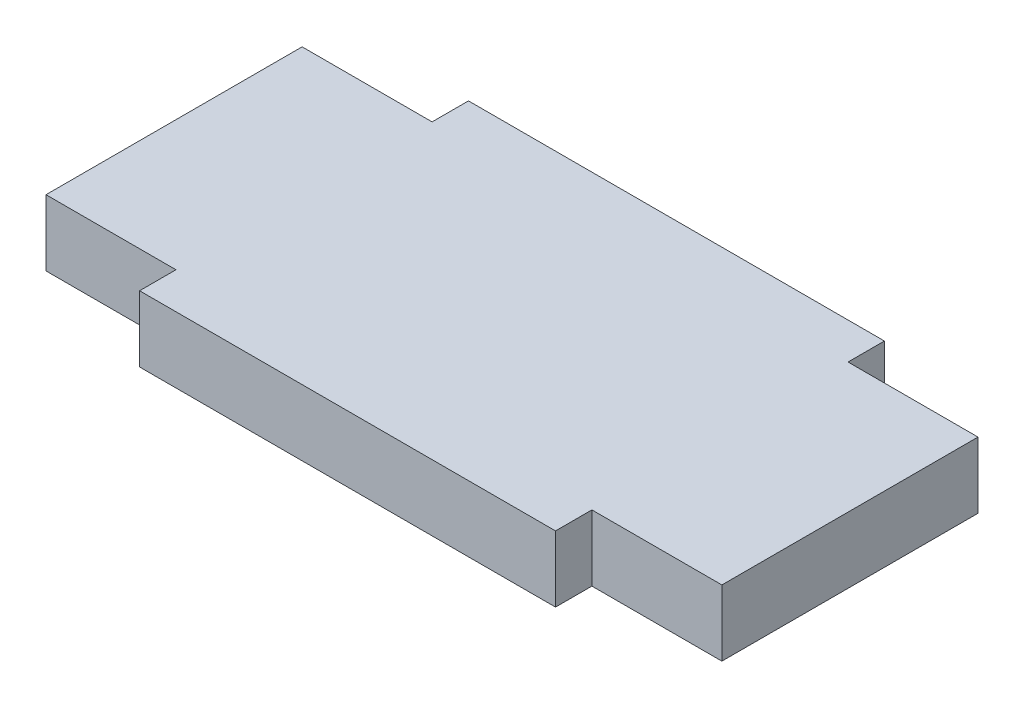
SolidWorks part; units mm, degrees
material "Acrylic (Medium-high impact)"
ref_plane "Front Plane" through (0, 0, 0) normal (0, 0, 1) x (1, 0, 0)
ref_plane "Top Plane" through (0, 0, 0) normal (0, 1, 0) x (1, 0, 0)
ref_plane "Right Plane" through (0, 0, 0) normal (1, 0, 0) x (0, 0, -1)
sketch "Sketch1" plane through (0, 0, 0) normal (0, 1, 0) x (1, 0, 0)
  line L0 (0, -55) -> (0, 55) construction
  line L1 (-32, 20.645) -> (33, 20.645)
  line L2 (-32, 20.645) -> (-32, -10.985)
  line L3 (-32, -10.985) -> (33, -10.985)
  line L4 (33, 20.645) -> (33, -10.985)
  line L7 (33, 20.645) -> (20.5, 20.645)
  line L8 (33, 20.645) -> (33, 17.145)
  line L9 (33, 17.145) -> (20.5, 17.145)
  line L10 (20.5, 20.645) -> (20.5, 17.145)
  line L11 (-32, 20.645) -> (-19.5, 20.645)
  line L12 (-32, 20.645) -> (-32, 17.145)
  line L13 (-32, 17.145) -> (-19.5, 17.145)
  line L14 (-19.5, 20.645) -> (-19.5, 17.145)
  line L15 (-32, -10.985) -> (-19.5, -10.985)
  line L16 (-32, -10.985) -> (-32, -7.485)
  line L17 (-32, -7.485) -> (-19.5, -7.485)
  line L18 (-19.5, -10.985) -> (-19.5, -7.485)
  line L19 (33, -10.985) -> (20.5, -10.985)
  line L20 (33, -10.985) -> (33, -7.485)
  line L21 (33, -7.485) -> (20.5, -7.485)
  line L22 (20.5, -10.985) -> (20.5, -7.485)
  dimension "D2" = 40
  dimension "D3" = 33
  dimension "D5" = 3.5
  dimension "D6" = 12.5
  dimension "D7" = 3.5
  dimension "D8" = 12.5
  dimension "D9" = 3.5
  dimension "D10" = 12.5
  dimension "D11" = 12.5
  dimension "D12" = 3.5
  dimension "24.63" = 24.63
extrude "Boss-Extrude1" add sketch "Sketch1" along normal blind 6.35 contours L3 L22 L21 L4 L9 L10 L1 L14 L13 L2 L17 L18
